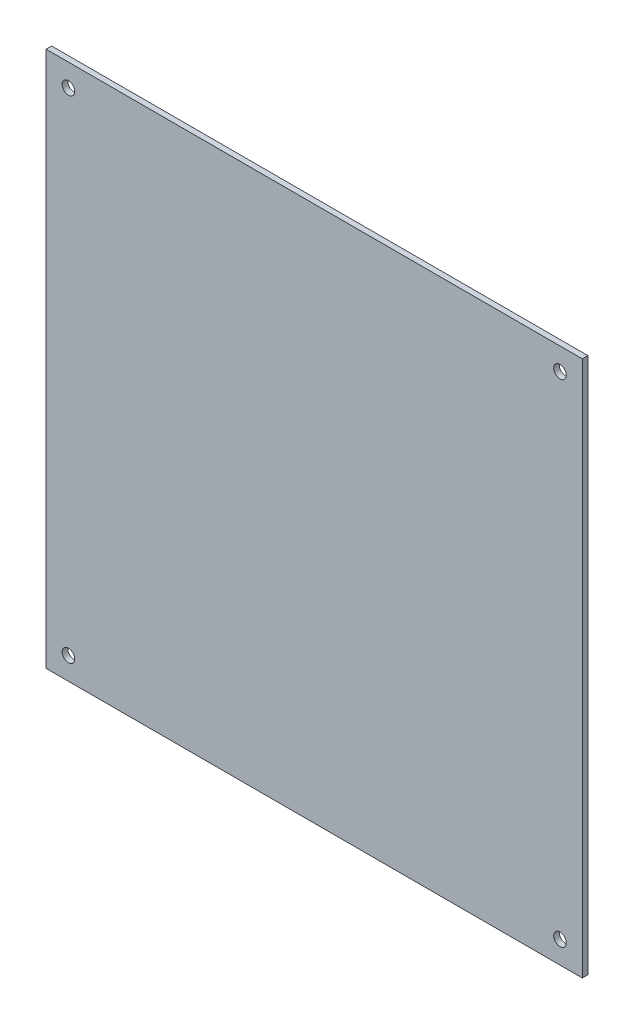
SolidWorks part; units mm, degrees
material "Acrylic (Medium-high impact)"
ref_plane "Front Plane" through (0, 0, 0) normal (0, 0, 1) x (1, 0, 0)
ref_plane "Top Plane" through (0, 0, 0) normal (0, 1, 0) x (1, 0, 0)
ref_plane "Right Plane" through (0, 0, 0) normal (1, 0, 0) x (0, 0, -1)
sketch "Sketch1" plane through (0, 0, 0) normal (0, 0, 1) x (1, 0, 0)
  line L1 (0, 0) -> (304.8, 0)
  line L2 (0, 0) -> (0, -304.8)
  line L3 (0, -304.8) -> (304.8, -304.8)
  line L4 (304.8, 0) -> (304.8, -304.8)
  dimension "D1" = 304.8
  dimension "D2" = 304.8
extrude "Boss-Extrude1" add sketch "Sketch1" along normal blind 3.175
sketch "Sketch2" plane through (0, 0, 3.175) normal (0, 0, 1) x (1, 0, 0)
  line L0 (152.4, 0) -> (152.4, -304.8) construction
  line L1 (304.8, 0) -> (0, 0) construction
  line L2 (0, -304.8) -> (304.8, -304.8) construction
  line L3 (0, -152.4) -> (304.8, -152.4) construction
  line L4 (0, 0) -> (0, -304.8) construction
  line L5 (304.8, -304.8) -> (304.8, 0) construction
  point P12 (12.7, -12.7)
  point P14 (292.1, -12.7)
  point P17 (12.7, -292.1)
  point P18 (292.1, -292.1)
  dimension "D1" = 12.7
  dimension "D2" = 12.7
hole_wizard "1/4 Clearance Hole1" positions "Sketch2" profile "Sketch3" hole size "1/4" standard "ANSI Inch" end condition up to next
sketch "Sketch3" plane through (292.1, -292.1, 3.175) normal (1, 0, 0) x (0, -1, 0)
  line L0 (0, 0) -> (0, 3.175)
  line L1 (0, 3.175) -> (3.5712, 3.175)
  line L2 (3.5712, 3.175) -> (3.5712, 0)
  line L5 (3.5712, 0) -> (0, 0)
  line L11 (0, -6.35) -> (0, 107.95) construction
  dimension "Thru Hole Dia." = 7.1425
  dimension "Thru Hole Depth" = 3.175
